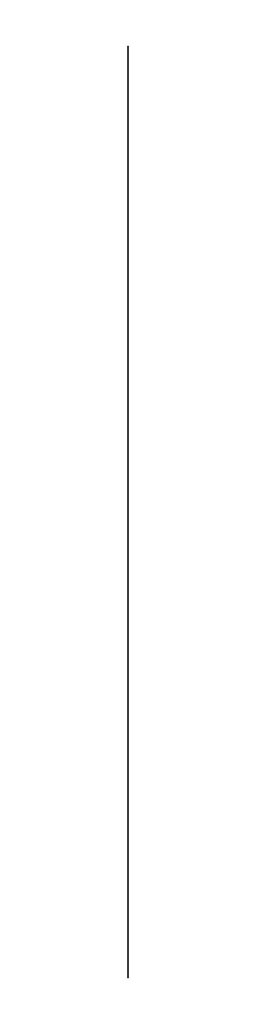
SolidWorks part; units mm, degrees
ref_plane "Front Plane" through (0, 0, 0) normal (0, 0, 1) x (1, 0, 0)
ref_plane "Top Plane" through (0, 0, 0) normal (0, 1, 0) x (1, 0, 0)
ref_plane "Right Plane" through (0, 0, 0) normal (1, 0, 0) x (0, 0, -1)
sketch "Sketch1" plane through (0, 0, 0) normal (0, 1, 0) x (1, 0, 0)
  circle A0 centre (0, 0) radius 0.05
  dimension "D1" = 0.1
extrude "Boss-Extrude1" add sketch "Sketch1" along normal blind 200
